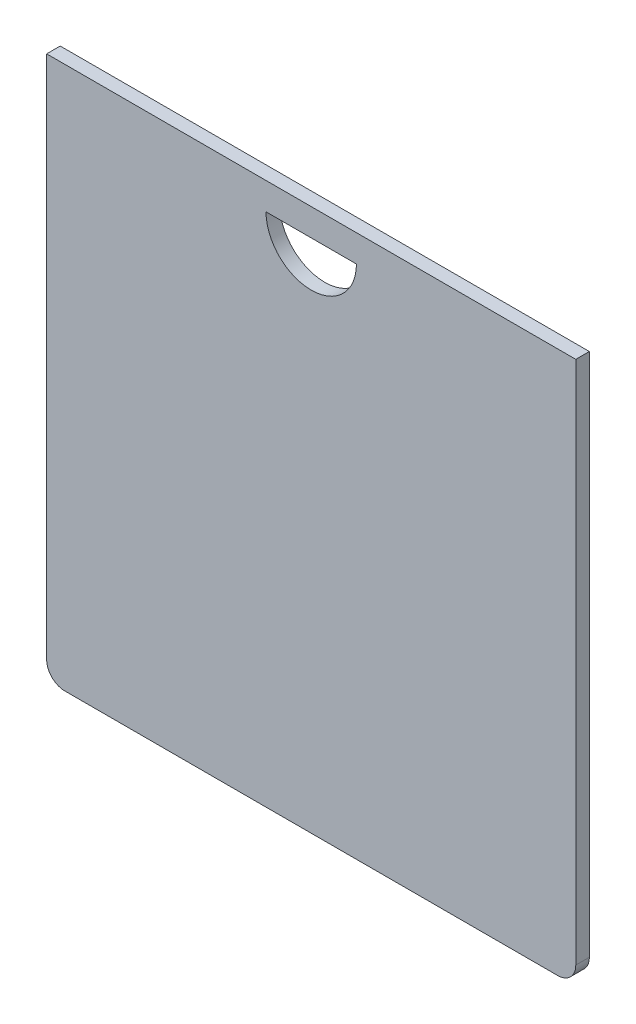
SolidWorks part; units mm, degrees
material "ABS"
ref_plane "Спереди" through (0, 0, 0) normal (0, 0, 1) x (1, 0, 0)
ref_plane "Сверху" through (0, 0, 0) normal (0, 1, 0) x (1, 0, 0)
ref_plane "Справа" through (0, 0, 0) normal (1, 0, 0) x (0, 0, -1)
sketch "Эскиз1" plane through (0, 0, 0) normal (0, 0, 1) x (1, 0, 0)
  line L1 (0, 60) -> (58.5, 60)
  line L2 (0, 60) -> (0, 0)
  line L3 (0, 0) -> (58.5, 0)
  line L4 (58.5, 60) -> (58.5, 0)
  dimension "D1" = 60
  dimension "D2" = 58.5
extrude "Бобышка-Вытянуть1" add sketch "Эскиз1" along normal blind 1.5
fillet "Скругление1" radius 2 2 edges at (58.5, 0, 0.75) (0, 0, 0.75)
sketch "Эскиз2" plane through (0, 0, 1.5) normal (0, 0, 1) x (1, 0, 0)
  line L0 (24.25, 57) -> (34.25, 57)
  line L1 (58.5, 60) -> (0, 60) construction
  arc A0 (24.25, 57) -> (34.25, 57) centre (29.25, 57) ccw
  point P7 (29.25, 60)
  dimension "D2" = 5
  dimension "D1" = 3
extrude "Вырез-Вытянуть1" cut sketch "Эскиз2" against normal through all
